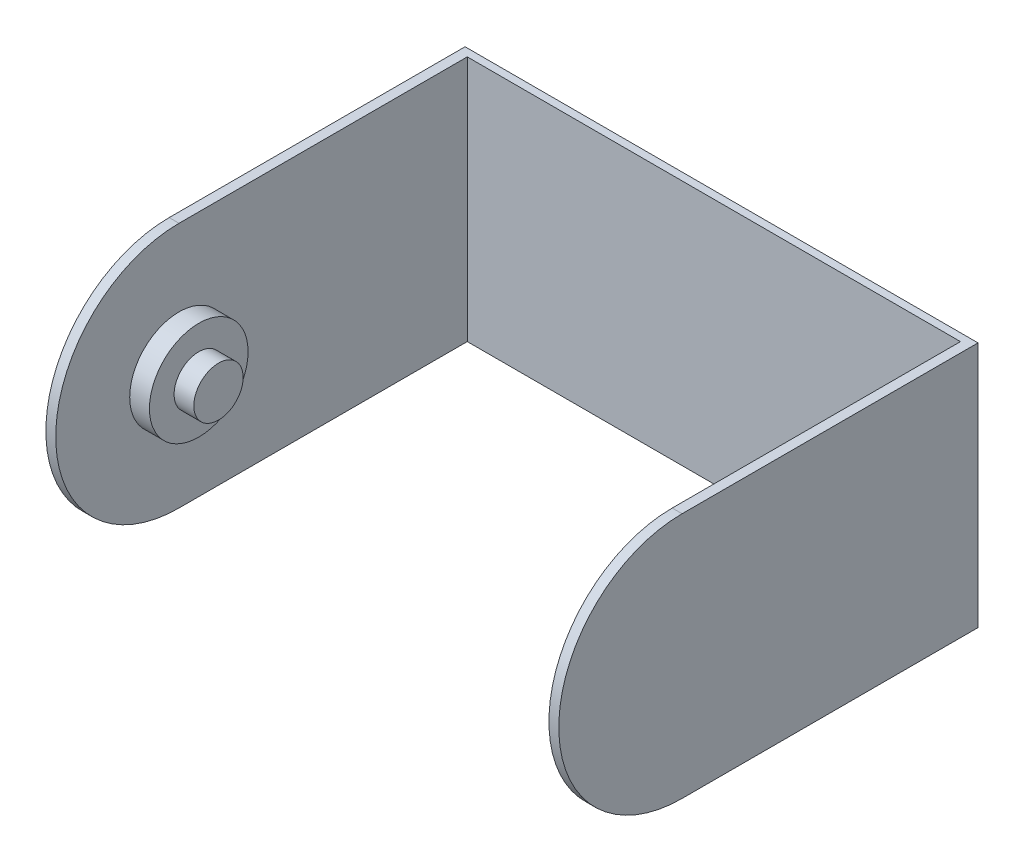
SolidWorks part; units mm, degrees
material "Plastique personnalisé"
ref_plane "Plan de face" through (0, 0, 0) normal (0, 0, 1) x (1, 0, 0)
ref_plane "Plan de dessus" through (0, 0, 0) normal (0, 1, 0) x (1, 0, 0)
ref_plane "Plan de droite" through (0, 0, 0) normal (1, 0, 0) x (0, 0, -1)
sketch "Esquisse1" plane through (0, 0, 0) normal (0, 1, 0) x (1, 0, 0)
  line L1 (-3.234, -21.9468) -> (-2.234, -21.9468)
  line L2 (-3.234, -21.9468) -> (-3.234, 8.0532)
  line L4 (-2.234, -21.9468) -> (-2.234, 7.2756)
  line L5 (-3.234, 8.0532) -> (48.766, 8.0532)
  line L7 (-2.234, 7.2756) -> (47.766, 7.2756)
  line L8 (48.766, 8.0532) -> (48.766, 7.2756)
  line L9 (48.766, 8.0532) -> (47.766, 8.0532)
  line L10 (48.766, 8.0532) -> (48.766, -21.9468)
  line L11 (48.766, -21.9468) -> (47.766, -21.9468)
  line L12 (47.766, 7.2756) -> (47.766, -21.9468)
  dimension "D2" = 30
  dimension "D4" = 1
extrude "Boss.-Extru.1" add sketch "Esquisse1" along normal blind 25 contours L10 L11 L12 L7 L4 L1 L2 L5
ref_plane "Plan1" through (-3.234, 0, 0) normal (-1, 0, 0) x (0, 0, 1)
sketch "Esquisse3" plane through (-3.234, 0, 0) normal (-1, 0, 0) x (0, 0, 1)
  line L0 (21.9468, 25) -> (21.9468, 0) construction
  line L1 (21.9468, 25) -> (21.9468, 0)
  arc A0 (21.9468, 0) -> (21.9468, 25) centre (21.9468, 12.5) ccw
extrude "Boss.-Extru.2" add sketch "Esquisse3" against normal blind 1
ref_plane "Plan2" through (48.766, 0, 0) normal (1, 0, 0) x (0, 0, -1)
sketch "Esquisse4" plane through (48.766, 0, 0) normal (1, 0, 0) x (0, 0, -1)
  line L0 (-21.9468, 25) -> (-21.9468, 0) construction
  line L1 (-21.9468, 25) -> (-21.9468, 0)
  arc A0 (-21.9468, 25) -> (-21.9468, 0) centre (-21.9468, 12.5) ccw
extrude "Boss.-Extru.3" add sketch "Esquisse4" against normal blind 1 contours A0 L1
ref_plane "Plan3" through (-2.234, 0, 0) normal (1, 0, 0) x (0, 0, -1)
sketch "Esquisse6" plane through (-2.234, 0, 0) normal (1, 0, 0) x (0, 0, -1)
  circle A0 centre (-21.9468, 12.222) radius 5
  arc A1 (-21.9468, 25) -> (-21.9468, 0) centre (-21.9468, 12.5) ccw construction
  dimension "D1" = 0
  dimension "D2" = 10
extrude "Boss.-Extru.4" add sketch "Esquisse6" along normal blind 2
ref_plane "Plan4" through (-0.234, 0, 0) normal (1, 0, 0) x (0, 0, -1)
sketch "Esquisse7" plane through (-0.234, 0, 0) normal (1, 0, 0) x (0, 0, -1)
  circle A0 centre (-21.9468, 12.222) radius 2.5
  dimension "D1" = 5
extrude "Boss.-Extru.5" add sketch "Esquisse7" along normal blind 2 contours A0
